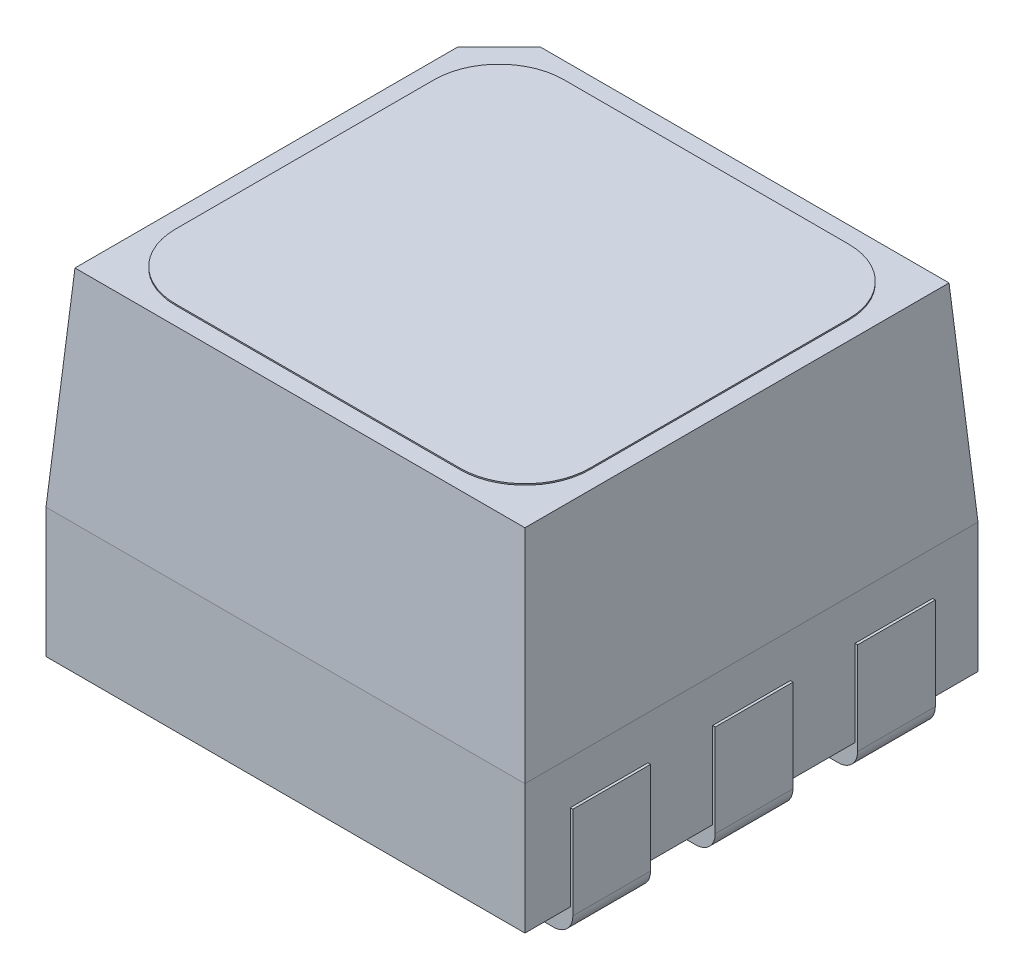
SolidWorks part; units mm, degrees
ref_plane "Plan de face" through (0, 0, 0) normal (0, 0, 1) x (1, 0, 0)
ref_plane "Plan de dessus" through (0, 0, 0) normal (0, 1, 0) x (1, 0, 0)
ref_plane "Plan de droite" through (0, 0, 0) normal (1, 0, 0) x (0, 0, -1)
sketch "Esquisse1" plane through (0, 0, 0) normal (0, 1, 0) x (1, 0, 0)
  line L0 (-2.4601, 0) -> (2.4011, 0) construction
  line L1 (0, 2.3519) -> (0, -2.1551) construction
  line L3 (-1.85, -1.75) -> (1.85, -1.75)
  line L4 (-1.85, -1.75) -> (-1.85, 1.75)
  line L5 (-1.85, 1.75) -> (1.85, 1.75)
  line L6 (1.85, -1.75) -> (1.85, 1.75)
  line L7 (-1.85, -1.75) -> (1.85, 1.75) construction
  line L8 (-1.85, 1.75) -> (1.85, -1.75) construction
  point P5 (0, 0)
  dimension "D1" = 3.7
  dimension "D2" = 3.5
extrude "Boss.-Extru.1" add sketch "Esquisse1" along normal blind 1
sketch "Esquisse2" plane through (0, 1, 0) normal (0, 1, 0) x (1, 0, 0)
  line L1 (-1.85, -1.75) -> (1.85, -1.75)
  line L2 (-1.85, -1.75) -> (-1.85, 1.75)
  line L3 (-1.85, 1.75) -> (1.85, 1.75)
  line L4 (1.85, -1.75) -> (1.85, 1.75)
  line L5 (-1.85, -1.75) -> (1.85, 1.75) construction
  line L6 (-1.85, 1.75) -> (1.85, -1.75) construction
  point P1 (0, 0)
extrude "Boss.-Extru.2" add sketch "Esquisse2" along normal blind 1.6 draft 4 separate body
sketch "Esquisse3" plane through (0, 2.6, 0) normal (0, 1, 0) x (1, 0, 0)
  line L1 (-1.1, -1.5) -> (1.1, -1.5)
  line L2 (-1.6, -1) -> (-1.6, 1)
  line L3 (-1.1, 1.5) -> (1.1, 1.5)
  line L4 (1.6, -1) -> (1.6, 1)
  line L5 (-1.6, -1.5) -> (1.6, 1.5) construction
  line L6 (-1.6, 1.5) -> (1.6, -1.5) construction
  arc A0 (-1.6, -1) -> (-1.1, -1.5) centre (-1.1, -1) ccw
  arc A1 (1.1, -1.5) -> (1.6, -1) centre (1.1, -1) ccw
  arc A2 (1.1, 1.5) -> (1.6, 1) centre (1.1, 1) cw
  arc A3 (-1.1, 1.5) -> (-1.6, 1) centre (-1.1, 1) ccw
  point P0 (0, 0)
  dimension "D3" = 0.5
  dimension "D1" = 3.2
  dimension "D2" = 3
extrude "Boss.-Extru.3" add sketch "Esquisse3" along normal blind 0.01
sketch "Esquisse4" plane through (0, 2.6, 0) normal (0, 1, 0) x (1, 0, 0)
  line L0 (1.9059, -1.7632) -> (1.9059, -1.1516)
  line L2 (1.9059, -1.1516) -> (1.2952, -1.7632)
  line L4 (1.2952, -1.7632) -> (1.9059, -1.7632)
extrude "Enlèv. mat.-Extru.2" cut sketch "Esquisse4" against normal blind 0.5
sketch "Esquisse5" plane through (0, 0, 0) normal (0, -1, 0) x (1, 0, 0)
  line L0 (0, 0) -> (-2.8715, 0) construction
  line L1 (-1.05, -0.3) -> (-1.85, -0.3)
  line L2 (-1.05, -0.3) -> (-1.05, 0.3)
  line L3 (-1.05, 0.3) -> (-1.85, 0.3)
  line L4 (-1.85, -0.3) -> (-1.85, 0.3)
  line L5 (-1.05, -0.3) -> (-1.85, 0.3) construction
  line L6 (-1.05, 0.3) -> (-1.85, -0.3) construction
  line L7 (1.05, -0.3) -> (1.85, -0.3)
  line L8 (1.05, -0.3) -> (1.05, 0.3)
  line L9 (1.05, 0.3) -> (1.85, 0.3)
  line L10 (1.85, -0.3) -> (1.85, 0.3)
  line L11 (1.05, -0.3) -> (1.85, 0.3) construction
  line L12 (1.05, 0.3) -> (1.85, -0.3) construction
  line L13 (-2.8715, 0) -> (2.2685, 0) construction
  line L14 (0, 1.9164) -> (0, -1.9756) construction
  line L15 (1.85, 1.75) -> (1.85, -1.75) construction
  line L16 (1.05, 0.8) -> (1.85, 0.8)
  line L17 (1.05, 0.8) -> (1.05, 1.4)
  line L18 (1.05, 1.4) -> (1.85, 1.4)
  line L19 (1.85, 0.8) -> (1.85, 1.4)
  line L20 (1.05, 0.8) -> (1.85, 1.4) construction
  line L21 (1.05, 1.4) -> (1.85, 0.8) construction
  line L23 (-1.85, 0.8) -> (-1.05, 0.8)
  line L24 (-1.85, 0.8) -> (-1.85, 1.4)
  line L25 (-1.85, 1.4) -> (-1.05, 1.4)
  line L26 (-1.05, 0.8) -> (-1.05, 1.4)
  line L27 (-1.85, 0.8) -> (-1.05, 1.4) construction
  line L28 (-1.85, 1.4) -> (-1.05, 0.8) construction
  line L29 (1.85, -1.4) -> (1.05, -1.4)
  line L30 (1.85, -1.4) -> (1.85, -0.8)
  line L31 (1.85, -0.8) -> (1.05, -0.8)
  line L32 (1.05, -1.4) -> (1.05, -0.8)
  line L33 (1.85, -1.4) -> (1.05, -0.8) construction
  line L34 (1.85, -0.8) -> (1.05, -1.4) construction
  line L35 (-1.85, -1.4) -> (-1.05, -1.4)
  line L36 (-1.85, -1.4) -> (-1.85, -0.8)
  line L37 (-1.85, -0.8) -> (-1.05, -0.8)
  line L38 (-1.05, -1.4) -> (-1.05, -0.8)
  line L39 (-1.85, -1.4) -> (-1.05, -0.8) construction
  line L40 (-1.85, -0.8) -> (-1.05, -1.4) construction
  point P0 (-1.45, 0)
  point P5 (1.45, 0)
  point P16 (1.45, 1.1)
  point P23 (-1.45, 1.1)
  point P28 (1.45, -1.1)
  point P33 (-1.45, -1.1)
  dimension "D1" = 0.6
  dimension "D2" = 0.8
  dimension "D3" = 0.8
  dimension "D4" = 0.6
  dimension "D5" = 1.05
  dimension "D6" = 1.05
  dimension "D7" = 0.6
  dimension "D8" = 0.6
  dimension "D9" = 0.6
  dimension "D10" = 0.6
  dimension "D11" = 1.4
  dimension "D12" = 1.4
  dimension "D13" = 1.4
  dimension "D14" = 1.4
extrude "Boss.-Extru.4" add sketch "Esquisse5" along normal blind 0.2
sketch "Esquisse6" plane through (-1.85, 0, 0) normal (-1, 0, 0) x (0, 0, 1)
  line L1 (-1.4, -0.2) -> (-0.8, -0.2)
  line L2 (-1.4, -0.2) -> (-1.4, 0.664)
  line L3 (-1.4, 0.664) -> (-0.8, 0.664)
  line L4 (-0.8, -0.2) -> (-0.8, 0.664)
  line L5 (-0.3, -0.2) -> (0.3, -0.2)
  line L6 (-0.3, -0.2) -> (-0.3, 0.664)
  line L7 (-0.3, 0.664) -> (0.3, 0.664)
  line L8 (0.3, -0.2) -> (0.3, 0.664)
  line L9 (0.8, -0.2) -> (1.4, -0.2)
  line L10 (0.8, -0.2) -> (0.8, 0.664)
  line L11 (0.8, 0.664) -> (1.4, 0.664)
  line L12 (1.4, -0.2) -> (1.4, 0.664)
extrude "Enlèv. mat.-Extru.3" cut sketch "Esquisse6" against normal blind 0.2
sketch "Esquisse8" plane through (1.85, 0, 0) normal (1, 0, 0) x (0, 0, -1)
  line L1 (-1.4, -0.2) -> (-0.8, -0.2)
  line L2 (-1.4, -0.2) -> (-1.4, 0.6004)
  line L3 (-1.4, 0.6004) -> (-0.8, 0.6004)
  line L4 (-0.8, -0.2) -> (-0.8, 0.6004)
  line L5 (-0.3, -0.2) -> (0.3, -0.2)
  line L6 (-0.3, -0.2) -> (-0.3, 0.6004)
  line L7 (-0.3, 0.6004) -> (0.3, 0.6004)
  line L8 (0.3, -0.2) -> (0.3, 0.6004)
  line L9 (0.8, -0.2) -> (1.4, -0.2)
  line L10 (0.8, -0.2) -> (0.8, 0.6004)
  line L11 (0.8, 0.6004) -> (1.4, 0.6004)
  line L12 (1.4, -0.2) -> (1.4, 0.6004)
extrude "Enlèv. mat.-Extru.4" cut sketch "Esquisse8" against normal blind 0.2
sketch "Esquisse9" plane through (-1.65, 0, 0) normal (-1, 0, 0) x (0, 0, 1)
  line L1 (-1.4, -0.2) -> (-0.8, -0.2)
  line L2 (-1.4, -0.2) -> (-1.4, 0.664)
  line L3 (-1.4, 0.664) -> (-0.8, 0.664)
  line L4 (-0.8, -0.2) -> (-0.8, 0.664)
  line L5 (-0.3, -0.2) -> (0.3, -0.2)
  line L6 (-0.3, -0.2) -> (-0.3, 0.664)
  line L7 (-0.3, 0.664) -> (0.3, 0.664)
  line L8 (0.3, -0.2) -> (0.3, 0.664)
  line L9 (0.8, -0.2) -> (1.4, -0.2)
  line L10 (0.8, -0.2) -> (0.8, 0.664)
  line L11 (0.8, 0.664) -> (1.4, 0.664)
  line L12 (1.4, -0.2) -> (1.4, 0.664)
extrude "Boss.-Extru.5" add sketch "Esquisse9" along normal blind 0.22
sketch "Esquisse10" plane through (1.65, 0, 0) normal (1, 0, 0) x (0, 0, -1)
  line L1 (-1.4, -0.2) -> (-0.8, -0.2)
  line L2 (-1.4, -0.2) -> (-1.4, 0.6004)
  line L3 (-1.4, 0.6004) -> (-0.8, 0.6004)
  line L4 (-0.8, -0.2) -> (-0.8, 0.6004)
  line L5 (-0.3, -0.2) -> (0.3, -0.2)
  line L6 (-0.3, -0.2) -> (-0.3, 0.6004)
  line L7 (-0.3, 0.6004) -> (0.3, 0.6004)
  line L8 (0.3, -0.2) -> (0.3, 0.6004)
  line L9 (0.8, -0.2) -> (1.4, -0.2)
  line L10 (0.8, -0.2) -> (0.8, 0.6004)
  line L11 (0.8, 0.6004) -> (1.4, 0.6004)
  line L12 (1.4, -0.2) -> (1.4, 0.6004)
extrude "Boss.-Extru.6" add sketch "Esquisse10" along normal blind 0.22
sketch "Esquisse12" plane through (0, 0, 1.4) normal (0, 0, 1) x (1, 0, 0)
  line L0 (-1.05, 0) -> (-1.85, 0) construction
  line L1 (-1.72, -0.2) -> (-2.0514, -0.2)
  line L2 (-1.87, -0.05) -> (-1.87, 0)
  line L3 (-1.87, 0) -> (-2.0514, 0)
  line L4 (-2.0514, -0.2) -> (-2.0514, 0)
  line L5 (-1.85, 0) -> (1.85, 0) construction
  line L6 (1.72, -0.2) -> (2.0463, -0.2)
  line L7 (1.87, -0.05) -> (1.87, 0)
  line L8 (1.87, 0) -> (2.0463, 0)
  line L9 (2.0463, -0.2) -> (2.0463, 0)
  arc A0 (1.72, -0.2) -> (1.87, -0.05) centre (1.72, -0.05) ccw
  arc A1 (-1.72, -0.2) -> (-1.87, -0.05) centre (-1.72, -0.05) cw
  point P16 (1.87, -0.2)
  point P19 (-1.87, -0.2)
  dimension "D1" = 0.15
extrude "Enlèv. mat.-Extru.5" cut sketch "Esquisse12" against normal through all
sketch "Esquisse13" plane through (0, -0.2, 0) normal (0, -1, 0) x (1, 0, 0)
  point P0 (0, 0)
move or copy body "Corps-Déplacer/Copier1" bodies to move or copy 105 113 copy no rotation origin (0, 0, 0) rotation axis (0, 1, 0) rotation angle 180
